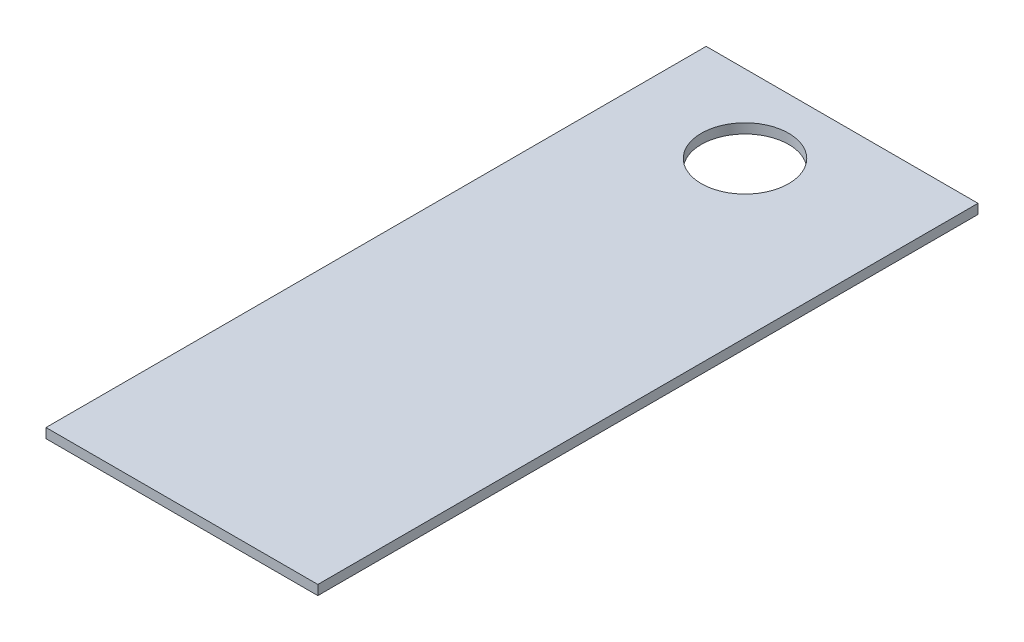
SolidWorks part; units mm, degrees
ref_plane "Front Plane" through (0, 0, 0) normal (0, 0, 1) x (1, 0, 0)
ref_plane "Top Plane" through (0, 0, 0) normal (0, 1, 0) x (1, 0, 0)
ref_plane "Right Plane" through (0, 0, 0) normal (1, 0, 0) x (0, 0, -1)
sketch "Sketch1" plane through (0, 0, 0) normal (0, 1, 0) x (1, 0, 0)
  line L0 (-6.35, 82.55) -> (44.45, 82.55) construction
  line L1 (-44.45, -107.95) -> (44.45, -107.95)
  line L2 (-44.45, -107.95) -> (-44.45, 107.95)
  line L3 (-44.45, 107.95) -> (44.45, 107.95)
  line L4 (44.45, -31.75) -> (44.45, 107.95)
  line L5 (-44.45, -107.95) -> (44.45, 107.95) construction
  line L6 (-44.45, 107.95) -> (44.45, -107.95) construction
  line L7 (-6.35, 107.95) -> (-6.35, 82.55) construction
  line L11 (44.45, -31.75) -> (44.45, -107.95)
  circle A0 centre (-6.35, 82.55) radius 14.2875
  point P0 (0, 0)
  dimension "D3" = 28.575
  dimension "D1" = 215.9
  dimension "D2" = 88.9
  dimension "D4" = 38.1
  dimension "D5" = 190.5
  dimension "D8" = 215.9
extrude "Boss-Extrude1" add sketch "Sketch1" along normal blind 3.175
